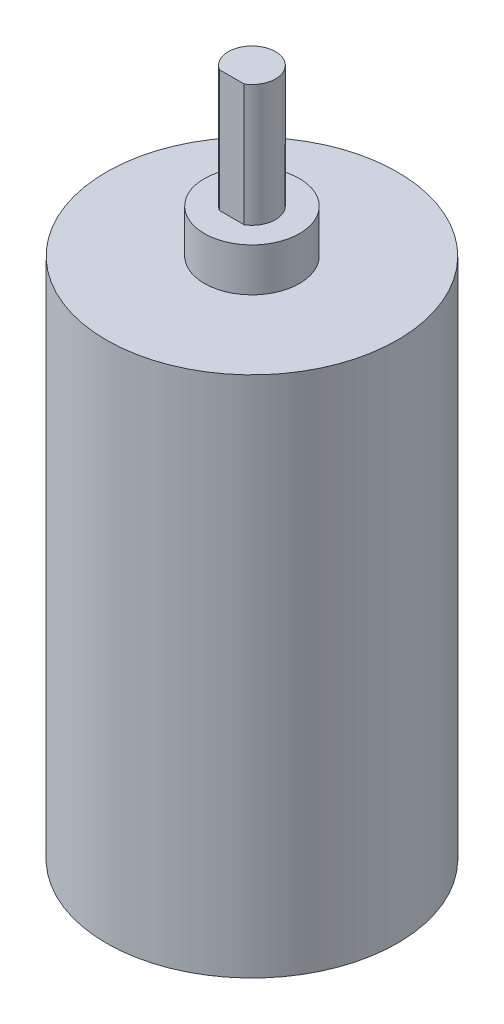
SolidWorks part; units mm, degrees
ref_plane "Front Plane" through (0, 0, 0) normal (0, 0, 1) x (1, 0, 0)
ref_plane "Top Plane" through (0, 0, 0) normal (0, 1, 0) x (1, 0, 0)
ref_plane "Right Plane" through (0, 0, 0) normal (1, 0, 0) x (0, 0, -1)
sketch "Sketch1" plane through (0, 0, 0) normal (0, 1, 0) x (1, 0, 0)
  circle A0 centre (0, 0) radius 185
extrude "Boss-Extrude1" add sketch "Sketch1" along normal blind 664
sketch "Sketch2" plane through (0, 664, 0) normal (0, 1, 0) x (1, 0, 0)
  circle A0 centre (0, 0) radius 60.5
extrude "Boss-Extrude2" add sketch "Sketch2" along normal blind 55
sketch "Sketch3" plane through (0, 719, 0) normal (0, 1, 0) x (1, 0, 0)
  line L1 (0, -25.5642) -> (15.6995, -25.5642)
  line L2 (0, -25.5642) -> (-15.6995, -25.5642)
  arc A0 (15.6995, -25.5642) -> (-15.6995, -25.5642) centre (0, 0) ccw
extrude "Boss-Extrude3" add sketch "Sketch3" along normal blind 155
scale "Scale1" scale about centroid uniform scaling yes scale factor 0.1
